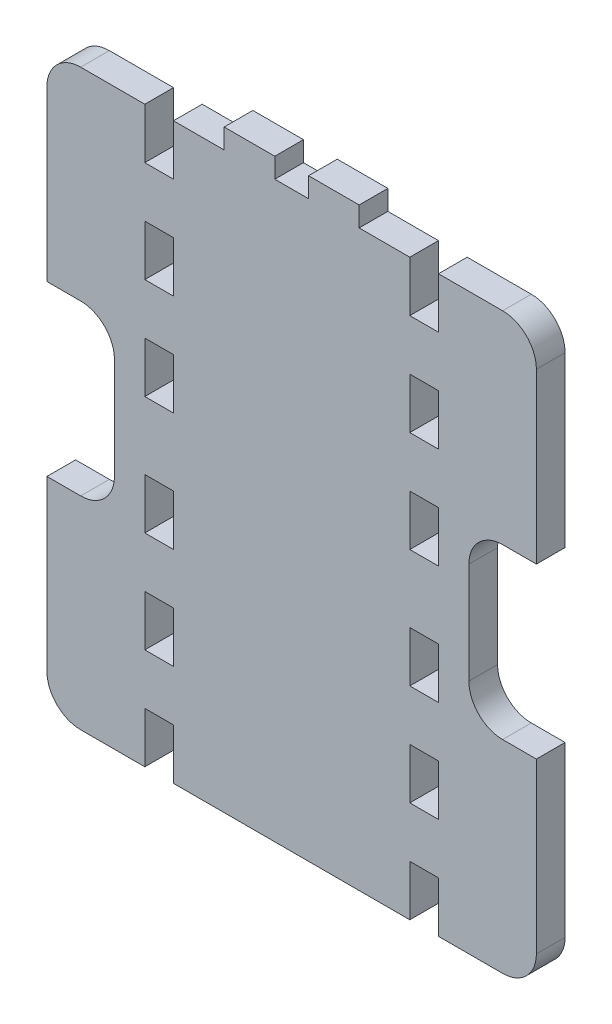
SolidWorks part; units mm, degrees
ref_plane "Front Plane" through (0, 0, 0) normal (0, 0, 1) x (1, 0, 0)
ref_plane "Top Plane" through (0, 0, 0) normal (0, 1, 0) x (1, 0, 0)
ref_plane "Right Plane" through (0, 0, 0) normal (1, 0, 0) x (0, 0, -1)
sketch "Sketch1" plane through (0, 0, 0) normal (0, 0, 1) x (1, 0, 0)
  line L0 (-125, -170) -> (-87, -170)
  line L1 (-70, -170) -> (-70, -140)
  line L2 (-145, -150) -> (-145, -50)
  line L3 (-125, 170) -> (-87, 170)
  line L4 (145, -150) -> (145, -50)
  line L5 (-70, -140) -> (-87, -140)
  line L6 (-87, -140) -> (-87, -170)
  line L7 (-70, 170) -> (-40, 170)
  line L8 (-87, -110) -> (-70, -110)
  line L9 (-125, 170) -> (-87, 170)
  line L10 (-70, -110) -> (-70, -80)
  line L11 (-70, -80) -> (-87, -80)
  line L12 (-87, -80) -> (-87, -110)
  line L13 (87, 170) -> (125, 170)
  line L14 (-87, -50) -> (-70, -50)
  line L15 (70, 140) -> (70, 170)
  line L16 (-87, -50) -> (-87, -20)
  line L17 (-87, -20) -> (-70, -20)
  line L18 (-70, -20) -> (-70, -50)
  line L19 (87, 140) -> (87, 170)
  line L20 (-87, 20) -> (-70, 20)
  line L21 (70, 140) -> (87, 140)
  line L22 (-87, 20) -> (-87, 50)
  line L23 (-87, 50) -> (-70, 50)
  line L24 (-70, 50) -> (-70, 20)
  line L25 (70, 110) -> (70, 80)
  line L26 (-70, 80) -> (-87, 80)
  line L27 (87, 110) -> (70, 110)
  line L28 (-87, 80) -> (-87, 110)
  line L29 (-87, 110) -> (-70, 110)
  line L30 (-70, 110) -> (-70, 80)
  line L31 (87, 80) -> (87, 110)
  line L32 (-70, 140) -> (-87, 140)
  line L33 (70, 80) -> (87, 80)
  line L34 (-87, 140) -> (-87, 170)
  line L35 (-70, 140) -> (-70, 170)
  line L36 (70, 50) -> (70, 20)
  line L37 (87, 50) -> (70, 50)
  line L38 (87, 20) -> (87, 50)
  line L39 (87, 20) -> (70, 20)
  line L40 (70, -20) -> (70, -50)
  line L41 (87, -20) -> (70, -20)
  line L42 (87, -50) -> (87, -20)
  line L43 (87, -50) -> (70, -50)
  line L44 (87, -80) -> (87, -110)
  line L45 (70, -80) -> (87, -80)
  line L46 (70, -110) -> (70, -80)
  line L47 (87, -110) -> (70, -110)
  line L48 (87, -140) -> (87, -170)
  line L49 (70, -140) -> (87, -140)
  line L50 (70, -170) -> (70, -140)
  line L51 (125, -170) -> (87, -170)
  line L52 (70, -170) -> (40, -170)
  line L53 (-70, 170) -> (-40, 170)
  line L54 (87, 170) -> (125, 170)
  line L55 (-145, 50) -> (-145, 150)
  line L56 (145, 50) -> (145, 150)
  line L57 (105, 0) -> (105, 30)
  line L58 (105, 0) -> (105, -30)
  line L59 (125, -50) -> (145, -50)
  line L60 (125, 50) -> (145, 50)
  line L61 (10, -170) -> (-10, -170)
  line L62 (-125, -50) -> (-145, -50)
  line L63 (-125, 50) -> (-145, 50)
  line L64 (-105, 0) -> (-105, -30)
  line L65 (-105, 0) -> (-105, 30)
  line L66 (-40, -170) -> (-70, -170)
  line L67 (-10, 170) -> (10, 170)
  line L68 (40, 170) -> (70, 170)
  line L69 (40, 170) -> (70, 170)
  line L70 (145, 0) -> (45.951, 0)
  line L71 (-10, 170) -> (10, 170)
  line L74 (-40, 181.8) -> (-40, 170)
  line L75 (-10, 181.8) -> (-10, 170)
  line L76 (10, 181.8) -> (10, 170)
  line L77 (40, 181.8) -> (40, 170)
  line L78 (10, 181.8) -> (40, 181.8)
  line L79 (-40, 181.8) -> (-10, 181.8)
  line L80 (-40, -170) -> (40, -170)
  arc A0 (125, -50) -> (105, -30) centre (125, -30) cw
  arc A1 (105, 30) -> (125, 50) centre (125, 30) cw
  arc A2 (145, 150) -> (125, 170) centre (125, 150) ccw
  arc A3 (-125, 170) -> (-145, 150) centre (-125, 150) ccw
  arc A4 (145, -150) -> (125, -170) centre (125, -150) cw
  arc A5 (-125, -170) -> (-145, -150) centre (-125, -150) cw
  arc A6 (-125, -50) -> (-105, -30) centre (-125, -30) ccw
  arc A7 (-105, 30) -> (-125, 50) centre (-125, 30) ccw
  point P0 (0, 0)
  point P68 (105, 50)
  point P77 (145, -170)
  point P80 (-145, -170)
  dimension "D15" = 20
  dimension "D17" = 20
  dimension "D3" = 75
  dimension "D4" = 30
  dimension "D5" = 17
  dimension "D6" = 30
  dimension "D7" = 30
  dimension "D8" = 30
  dimension "D9" = 30
  dimension "D10" = 40
  dimension "D11" = 30
  dimension "D12" = 30
  dimension "D13" = 30
  dimension "D14" = 30
  dimension "D16" = 50
extrude "Boss-Extrude1" add sketch "Sketch1" along normal blind 17 contours A7 L65 L64 A6 L62 L2 A5 L0 L6 L5 L1 L52 L50 L49 L48 L51 A4 L4 L59 A0 L58 L57 A1 L60 L56 A2 L13 L19 L21 L15 L7 L35 L32 L34 L3 A3 L55 L63 L33 L25 L27 L31 L12 L11 L10 L8 L17 L18
